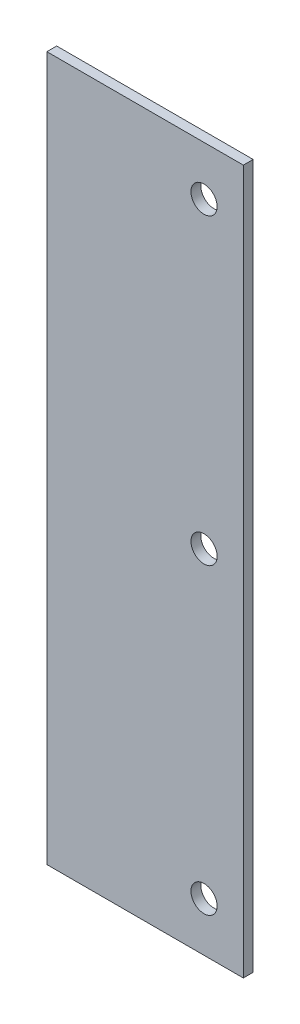
SolidWorks part; units mm, degrees
ref_plane "Front Plane" through (0, 0, 0) normal (0, 0, 1) x (1, 0, 0)
ref_plane "Top Plane" through (0, 0, 0) normal (0, 1, 0) x (1, 0, 0)
ref_plane "Right Plane" through (0, 0, 0) normal (1, 0, 0) x (0, 0, -1)
sketch "Sketch1" plane through (0, 0, 0) normal (0, 0, 1) x (1, 0, 0)
  line L0 (60, 215) -> (0, 215)
  line L1 (60, 215) -> (60, 0)
  line L2 (60, 0) -> (0, 0)
  line L3 (0, 215) -> (0, 0)
  circle A0 centre (48, 15) radius 4
  circle A1 centre (48, 107.5) radius 4
  circle A2 centre (48, 200) radius 4
  point P10 (0, 0)
  dimension "D1" = 60
  dimension "D2" = 8
  dimension "D3" = 8
  dimension "D4" = 8
  dimension "D8" = 15
  dimension "D5" = 215
  dimension "D6" = 12
  dimension "D7" = 15
  dimension "D9" = 107.5
extrude "Boss-Extrude1" add sketch "Sketch1" along normal blind 3
